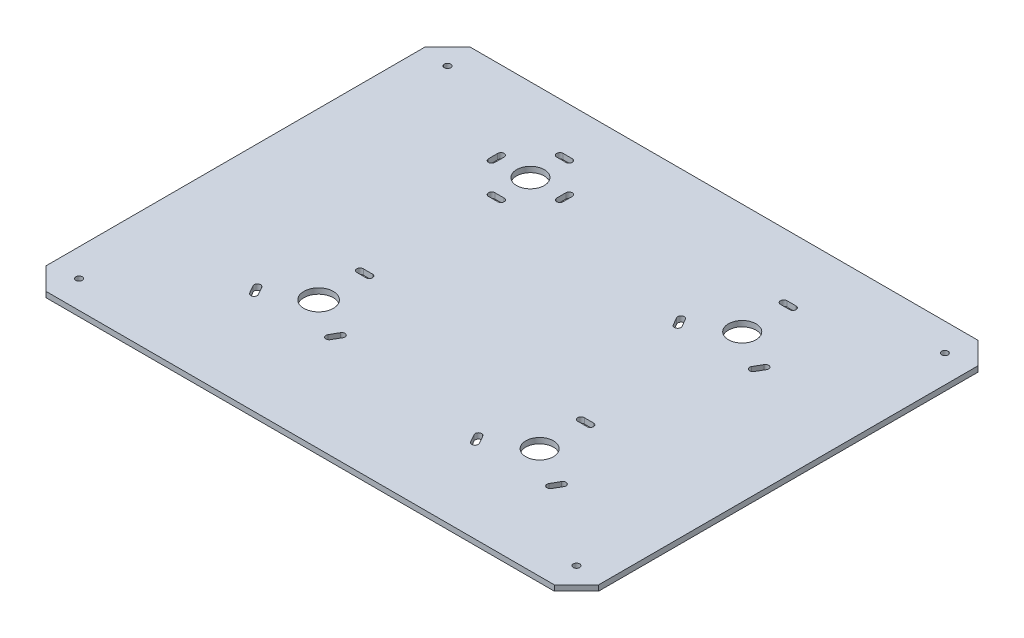
SolidWorks part; units mm, degrees
ref_plane "Plano frontal" through (0, 0, 0) normal (0, 0, 1) x (1, 0, 0)
ref_plane "Plano superior" through (0, 0, 0) normal (0, 1, 0) x (1, 0, 0)
ref_plane "Plano direito" through (0, 0, 0) normal (1, 0, 0) x (0, 0, -1)
sketch "Esboço1" plane through (0, 0, 0) normal (0, 1, 0) x (1, 0, 0)
  line L1 (-150, -115) -> (150, -115)
  line L2 (-150, -115) -> (-150, 115)
  line L3 (-150, 115) -> (150, 115)
  line L4 (150, -115) -> (150, 115)
  line L5 (-150, -115) -> (150, 115) construction
  line L6 (-150, 115) -> (150, -115) construction
  point P0 (0, 0)
  dimension "D1" = 300
  dimension "D2" = 230
extrude "Ressalto-extrusão1" add sketch "Esboço1" against normal blind 3
chamfer "Chanfro1" distance 12 angle 45 4 edges at (150, -1.5, -115) (-150, -1.5, -115) (-150, -1.5, 115) (150, -1.5, 115)
sketch "Posicionamento" plane through (0, 0, 0) normal (0, 1, 0) x (1, 0, 0)
  line L0 (-150, 103) -> (-150, -103) construction
  line L1 (0, -105) -> (-120, -105) construction
  line L2 (0, -105) -> (0, 15) construction
  line L3 (0, 15) -> (-120, 15) construction
  line L4 (-120, -105) -> (-120, 15) construction
  line L5 (0, -105) -> (-120, 15) construction
  line L6 (0, 15) -> (-120, -105) construction
  line L7 (120, -105) -> (20, -105) construction
  line L8 (120, -105) -> (120, -5) construction
  line L9 (120, -5) -> (20, -5) construction
  line L10 (20, -105) -> (20, -5) construction
  line L11 (120, -105) -> (20, -5) construction
  line L12 (120, -5) -> (20, -105) construction
  line L13 (120, 5) -> (20, 5) construction
  line L14 (120, 5) -> (120, 105) construction
  line L15 (120, 105) -> (20, 105) construction
  line L16 (20, 5) -> (20, 105) construction
  line L17 (120, 5) -> (20, 105) construction
  line L18 (120, 105) -> (20, 5) construction
  line L19 (138, 115) -> (-138, 115) construction
  line L20 (-138, -115) -> (138, -115) construction
  line L21 (150, -103) -> (150, 103) construction
  circle A0 centre (-60, 70) radius 33 construction
  point P0 (-60, -45)
  point P5 (70, -55)
  point P10 (70, 55)
  dimension "D7" = 66
  dimension "D1" = 120
  dimension "D2" = 100
  dimension "D3" = 30
  dimension "D4" = 10
  dimension "D5" = 10
  dimension "D6" = 30
  dimension "D8" = 45
sketch "Esboço4" plane through (0, 0, 0) normal (0, 1, 0) x (1, 0, 0)
  line L0 (-150, 103) -> (-150, -103) construction
  line L1 (-138, -115) -> (138, -115) construction
  line L2 (-62.5, -21.75) -> (-57.5, -21.75)
  line L3 (-62.5, -18.25) -> (-57.5, -18.25)
  line L4 (-62.5, -20) -> (-57.5, -20) construction
  line L5 (-60, -20) -> (-60, -45) construction
  line L6 (-38.6149, -54.4599) -> (-41.1149, -58.7901)
  line L7 (-35.5838, -56.2099) -> (-38.0838, -60.5401)
  line L8 (-37.0994, -55.3349) -> (-39.5994, -59.6651) construction
  line L9 (-38.3494, -57.5) -> (-60, -45) construction
  line L10 (-78.8851, -58.7901) -> (-81.3851, -54.4599)
  line L11 (-81.9162, -60.5401) -> (-84.4162, -56.2099)
  line L12 (-80.4006, -59.6651) -> (-82.9006, -55.3349) construction
  line L13 (-81.6506, -57.5) -> (-60, -45) construction
  line L14 (67.5, -28.25) -> (72.5, -28.25)
  line L15 (67.5, -30) -> (72.5, -30) construction
  line L16 (70, -55) -> (70, -30) construction
  line L17 (48.3494, -67.5) -> (70, -55) construction
  line L18 (91.3851, -64.4599) -> (88.8851, -68.7901)
  line L19 (94.4162, -66.2099) -> (91.9162, -70.5401)
  line L20 (49.5994, -69.6651) -> (47.0994, -65.3349) construction
  line L21 (51.1149, -68.7901) -> (48.6149, -64.4599)
  line L22 (67.5, -31.75) -> (72.5, -31.75)
  line L23 (92.9006, -65.3349) -> (90.4006, -69.6651) construction
  line L24 (48.0838, -70.5401) -> (45.5838, -66.2099)
  line L25 (91.6506, -67.5) -> (70, -55) construction
  line L26 (67.5, 81.75) -> (72.5, 81.75)
  line L27 (67.5, 80) -> (72.5, 80) construction
  line L28 (48.3494, 42.5) -> (70, 55) construction
  line L29 (70, 80) -> (70, 55) construction
  line L30 (91.3851, 45.5401) -> (88.8851, 41.2099)
  line L31 (94.4162, 43.7901) -> (91.9162, 39.4599)
  line L32 (49.5994, 40.3349) -> (47.0994, 44.6651) construction
  line L33 (51.1149, 41.2099) -> (48.6149, 45.5401)
  line L34 (67.5, 78.25) -> (72.5, 78.25)
  line L35 (90.4006, 40.3349) -> (92.9006, 44.6651) construction
  line L36 (48.0838, 39.4599) -> (45.5838, 43.7901)
  line L37 (70, 55) -> (91.6506, 42.5) construction
  line L38 (150, -103) -> (150, 103) construction
  line L39 (138, 115) -> (-138, 115) construction
  line L40 (-62.5, 86.75) -> (-57.5, 86.75)
  line L41 (-62.5, 90.25) -> (-57.5, 90.25)
  line L42 (-62.5, 88.5) -> (-57.5, 88.5) construction
  line L43 (-60, 88.5) -> (-60, 70) construction
  line L44 (-43.25, 72.5) -> (-43.25, 67.5)
  line L45 (-39.75, 72.5) -> (-39.75, 67.5)
  line L46 (-41.5, 72.5) -> (-41.5, 67.5) construction
  line L47 (-41.5, 70) -> (-60, 70) construction
  line L48 (-57.5, 53.25) -> (-62.5, 53.25)
  line L49 (-57.5, 49.75) -> (-62.5, 49.75)
  line L50 (-57.5, 51.5) -> (-62.5, 51.5) construction
  line L51 (-60, 51.5) -> (-60, 70) construction
  line L52 (-76.75, 67.5) -> (-76.75, 72.5)
  line L53 (-80.25, 67.5) -> (-80.25, 72.5)
  line L54 (-78.5, 67.5) -> (-78.5, 72.5) construction
  line L55 (-78.5, 70) -> (-60, 70) construction
  circle A0 centre (-60, -45) radius 8
  arc A1 (-62.5, -18.25) -> (-62.5, -21.75) centre (-62.5, -20) ccw
  arc A2 (-57.5, -21.75) -> (-57.5, -18.25) centre (-57.5, -20) ccw
  arc A3 (-35.5838, -56.2099) -> (-38.6149, -54.4599) centre (-37.0994, -55.3349) ccw
  arc A4 (-41.1149, -58.7901) -> (-38.0838, -60.5401) centre (-39.5994, -59.6651) ccw
  arc A5 (-81.9162, -60.5401) -> (-78.8851, -58.7901) centre (-80.4006, -59.6651) ccw
  arc A6 (-81.3851, -54.4599) -> (-84.4162, -56.2099) centre (-82.9006, -55.3349) ccw
  arc A7 (88.8851, -68.7901) -> (91.9162, -70.5401) centre (90.4006, -69.6651) ccw
  arc A8 (48.0838, -70.5401) -> (51.1149, -68.7901) centre (49.5994, -69.6651) ccw
  arc A9 (94.4162, -66.2099) -> (91.3851, -64.4599) centre (92.9006, -65.3349) ccw
  arc A10 (67.5, -28.25) -> (67.5, -31.75) centre (67.5, -30) ccw
  arc A11 (72.5, -31.75) -> (72.5, -28.25) centre (72.5, -30) ccw
  arc A12 (48.6149, -64.4599) -> (45.5838, -66.2099) centre (47.0994, -65.3349) ccw
  circle A13 centre (70, -55) radius 7.5
  arc A14 (88.8851, 41.2099) -> (91.9162, 39.4599) centre (90.4006, 40.3349) ccw
  arc A15 (48.0838, 39.4599) -> (51.1149, 41.2099) centre (49.5994, 40.3349) ccw
  arc A16 (94.4162, 43.7901) -> (91.3851, 45.5401) centre (92.9006, 44.6651) ccw
  arc A17 (67.5, 81.75) -> (67.5, 78.25) centre (67.5, 80) ccw
  arc A18 (72.5, 78.25) -> (72.5, 81.75) centre (72.5, 80) ccw
  arc A19 (48.6149, 45.5401) -> (45.5838, 43.7901) centre (47.0994, 44.6651) ccw
  circle A20 centre (70, 55) radius 7.5
  circle A21 centre (-60, 70) radius 7.5
  arc A22 (-62.5, 90.25) -> (-62.5, 86.75) centre (-62.5, 88.5) ccw
  arc A23 (-57.5, 86.75) -> (-57.5, 90.25) centre (-57.5, 88.5) ccw
  arc A24 (-39.75, 72.5) -> (-43.25, 72.5) centre (-41.5, 72.5) ccw
  arc A25 (-43.25, 67.5) -> (-39.75, 67.5) centre (-41.5, 67.5) ccw
  arc A26 (-57.5, 49.75) -> (-57.5, 53.25) centre (-57.5, 51.5) ccw
  arc A27 (-62.5, 53.25) -> (-62.5, 49.75) centre (-62.5, 51.5) ccw
  arc A28 (-80.25, 67.5) -> (-76.75, 67.5) centre (-78.5, 67.5) ccw
  arc A29 (-76.75, 72.5) -> (-80.25, 72.5) centre (-78.5, 72.5) ccw
  point P74 (90.1351, -66.625)
  dimension "D1" = 16
  dimension "D5" = 3.5
  dimension "D8" = 15
  dimension "D10" = 3.5
  dimension "D12" = 15
  dimension "D14" = 3.5
  dimension "D18" = 3.5
  dimension "D20" = 3.5
  dimension "D28" = 3.5
  dimension "D38" = 15
  dimension "D39" = 3.5
  dimension "D2" = 90
  dimension "D3" = 70
  dimension "D4" = 5
  dimension "D6" = 25
  dimension "D9" = 5
  dimension "D11" = 25
  dimension "D13" = 5
  dimension "D15" = 25
  dimension "D16" = 25
  dimension "D17" = 120
  dimension "D19" = 5
  dimension "D21" = 5
  dimension "D22" = 120
  dimension "D23" = 25
  dimension "D24" = 60
  dimension "D25" = 80
  dimension "D26" = 25
  dimension "D27" = 25
  dimension "D29" = 3.5
  dimension "D30" = 5
  dimension "D31" = 5
  dimension "D32" = 120
  dimension "D33" = 120
  dimension "D34" = 60
  dimension "D35" = 30
  dimension "D36" = 30
  dimension "D37" = 30
  dimension "D40" = 5
  dimension "D41" = 18.5
  dimension "D43" = 45
  dimension "D7" = 3
  dimension "D42" = 4
extrude "Corte-extrusão1" cut sketch "Esboço4" against normal through all
sketch "Esboço5" plane through (0, 0, 0) normal (0, 1, 0) x (1, 0, 0)
  line L0 (-135, -100) -> (-144, -109) construction
  line L1 (-150, -103) -> (-138, -115) construction
  line L2 (-150, 103) -> (-150, -103) construction
  circle A0 centre (-135, -100) radius 1.75
  dimension "D2" = 3.5
  dimension "D1" = 90
  dimension "D3" = 15
extrude "Corte-extrusão2" cut sketch "Esboço5" against normal through all
mirror "Espelhar1" about plane through (0, 0, 0) normal (0, 0, 1) of "Corte-extrusão2"
mirror "Espelhar2" about plane through (0, 0, 0) normal (1, 0, 0) of "Corte-extrusão2", "Espelhar1"
